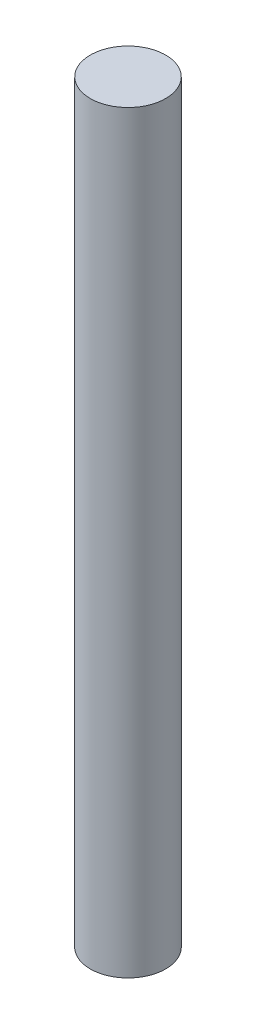
SolidWorks part; units mm, degrees
ref_plane "Front Plane" through (0, 0, 0) normal (0, 0, 1) x (1, 0, 0)
ref_plane "Top Plane" through (0, 0, 0) normal (0, 1, 0) x (1, 0, 0)
ref_plane "Right Plane" through (0, 0, 0) normal (1, 0, 0) x (0, 0, -1)
sketch "Sketch1" plane through (0, 0, 0) normal (0, 1, 0) x (1, 0, 0)
  circle A0 centre (0, 0) radius 12.7
extrude "Boss-Extrude1" add sketch "Sketch1" along normal blind 254
